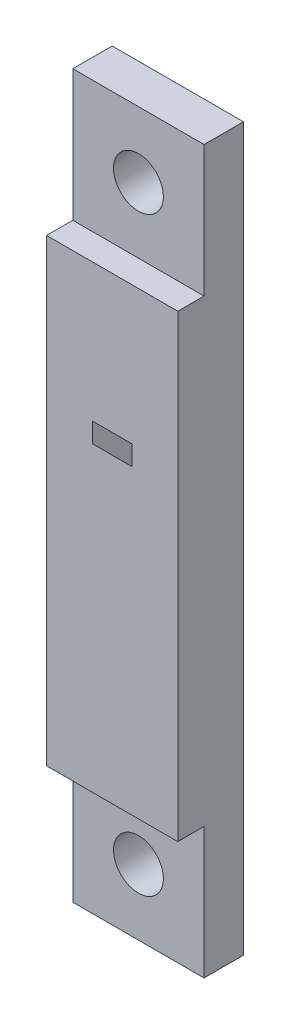
SolidWorks part; units mm, degrees
ref_plane "Front Plane" through (0, 0, 0) normal (0, 0, 1) x (1, 0, 0)
ref_plane "Top Plane" through (0, 0, 0) normal (0, 1, 0) x (1, 0, 0)
ref_plane "Right Plane" through (0, 0, 0) normal (1, 0, 0) x (0, 0, -1)
sketch "Sketch1" plane through (0, 0, 13.5) normal (0, 0, 1) x (1, 0, 0)
  line L0 (-2.1709, 0) -> (-6.6709, 0)
  line L1 (-2.1709, -2) -> (-2.1709, 2) construction
  line L2 (-6.6709, 2) -> (-6.6709, -2) construction
  line L4 (-9.4209, 27.5) -> (0.5791, 27.5)
  line L5 (-9.4209, 27.5) -> (-9.4209, -27.5)
  line L6 (-9.4209, -27.5) -> (0.5791, -27.5)
  line L7 (0.5791, 27.5) -> (0.5791, -27.5)
  line L8 (-9.4209, 27.5) -> (0.5791, -27.5) construction
  line L9 (-9.4209, -27.5) -> (0.5791, 27.5) construction
  point P6 (-4.4209, 0)
  line M5 (-6.6709, 2) -> (-6.6709, -2)
  line M6 (-6.6709, -2) -> (-2.1709, -2)
  line M7 (-2.1709, -2) -> (-2.1709, 2)
  line M8 (-2.1709, 2) -> (-6.6709, 2)
  dimension "D1" = 10
  dimension "D2" = 55
extrude "Boss-Extrude2" add sketch "Sketch1" along normal blind 5 contours L0 M7 M8 M5 | L0 M7 M5 M6 | L7 L4 L5 L6 M5 M8 M7 M6
sketch "Sketch2" plane through (0, 0, 18.5) normal (0, 0, 1) x (1, 0, 0)
  line L0 (-9.4209, 27.5) -> (-9.4209, -27.5) construction
  line L1 (0.5791, 27.5) -> (-9.4209, 27.5)
  line L2 (0.5791, 27.5) -> (0.5791, 17.5)
  line L3 (0.5791, 17.5) -> (-9.4209, 17.5)
  line L4 (-9.4209, 27.5) -> (-9.4209, 17.5)
  line L5 (0, 0) -> (-9.4209, 0)
  line L6 (-4.4209, 17.5) -> (-4.4209, 27.5)
  line L7 (0.5791, -17.5) -> (-9.4209, -17.5)
  line L8 (-9.4209, -27.5) -> (-9.4209, -17.5)
  line L9 (0.5791, -27.5) -> (-9.4209, -27.5)
  line L10 (0.5791, -27.5) -> (0.5791, -17.5)
  line M7 (0.5791, -27.5) -> (0.5791, 27.5)
  line M8 (0.5791, 27.5) -> (-9.4209, 27.5)
  line M9 (-9.4209, 27.5) -> (-9.4209, -27.5)
  line M10 (-9.4209, -27.5) -> (0.5791, -27.5)
  dimension "D1" = 10
extrude "Cut-Extrude1" cut sketch "Sketch2" against normal blind 2 contours L3 L6 L1 M9 | L6 L3 M7 M8 | L7 M7 M9 M10
sketch "Sketch3" plane through (0, 0, 16.5) normal (0, 0, 1) x (1, 0, 0)
  line L0 (-4.4209, 27.5) -> (-4.4209, 17.5)
  line L1 (0.5791, 27.5) -> (-9.4209, 27.5) construction
  line L2 (0.5791, 17.5) -> (-9.4209, 17.5) construction
  line L3 (-4.4209, -17.5) -> (-4.4209, -27.5)
  line L4 (0.5791, -17.5) -> (-9.4209, -17.5) construction
  line L5 (-9.4209, -27.5) -> (0.5791, -27.5) construction
  line L6 (-4.4209, 0) -> (0, 0)
  circle A0 centre (-4.4209, 22.5) radius 1.9
  circle A1 centre (-4.4209, -22.5) radius 1.9
  dimension "D1" = 3.8
extrude "Cut-Extrude2" cut sketch "Sketch3" against normal through all contours L0 A0 | L0 A0 | A1 L3 | A1 L3
sketch "Sketch4" plane through (0, 0, 13.5) normal (0, 0, -1) x (-1, 0, 0)
  line L0 (9.4209, 0) -> (-0.5791, 0)
  line L1 (9.4209, 27.5) -> (9.4209, -27.5) construction
  line L2 (-0.5791, 27.5) -> (-0.5791, -27.5) construction
  line L4 (2.9209, 2) -> (5.9209, 2)
  line L5 (2.9209, 2) -> (2.9209, -2)
  line L6 (2.9209, -2) -> (5.9209, -2)
  line L7 (5.9209, 2) -> (5.9209, -2)
  line L8 (2.9209, 2) -> (5.9209, -2) construction
  line L9 (2.9209, -2) -> (5.9209, 2) construction
  point P6 (4.4209, 0)
  dimension "D1" = 3
  dimension "D2" = 4
extrude "Cut-Extrude3" cut sketch "Sketch4" against normal blind 1.5 contours L7 L0 L5 L6 | L7 L4 L5 L0
sketch "Sketch5" plane through (-2.9209, 0, 0) normal (-1, 0, 0) x (0, 0, 1)
  line L0 (15, 2) -> (18.5, 5.5)
  line L1 (15, 2) -> (18.5, 2)
  line L2 (15, 3.5) -> (15, 5.5)
  line L3 (15, 5.5) -> (17, 5.5)
  line L4 (18.5, 2) -> (18.5, 5.5)
  line L5 (15, 2) -> (13.5, 2)
  line L6 (13.5, 2) -> (18.5, 7)
  line L7 (18.5, 7) -> (18.5, 5.5)
  line M8 (15, 2) -> (13.5, 2)
  dimension "D1" = 3.5
  dimension "D2" = 3.5
extrude "Cut-Extrude4" cut sketch "Sketch5" along normal blind 3 contours L7 L6 L0 M8
